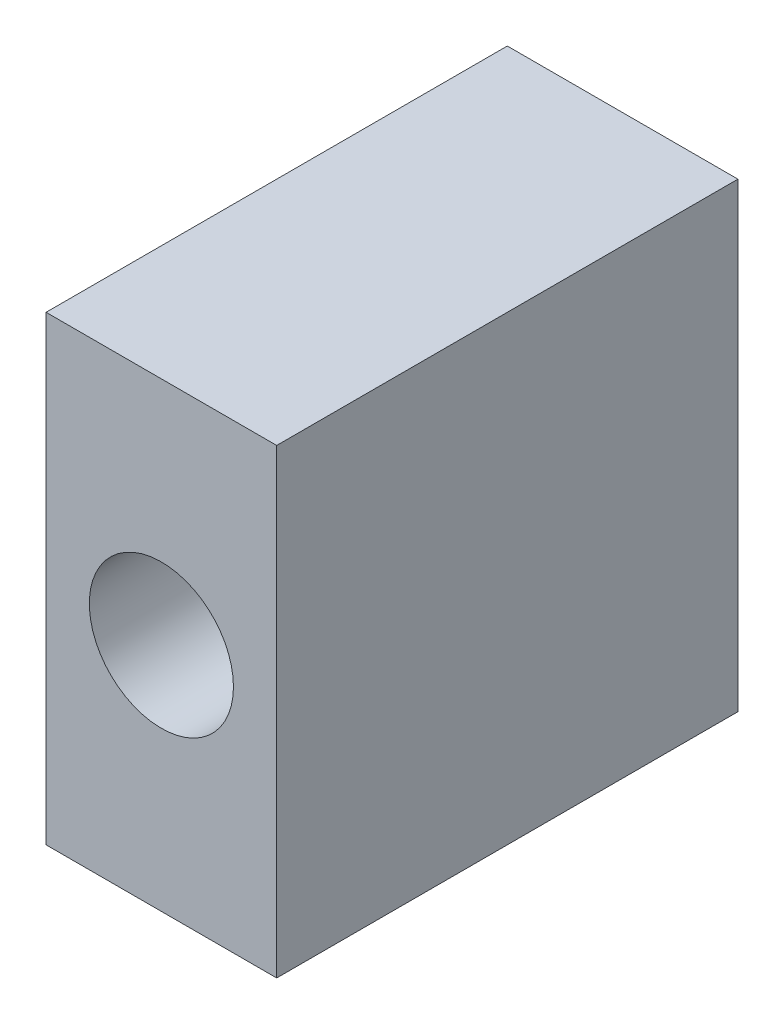
SolidWorks part; units mm, degrees
ref_plane "Front Plane" through (0, 0, 0) normal (0, 0, 1) x (1, 0, 0)
ref_plane "Top Plane" through (0, 0, 0) normal (0, 1, 0) x (1, 0, 0)
ref_plane "Right Plane" through (0, 0, 0) normal (1, 0, 0) x (0, 0, -1)
sketch "Sketch1" plane through (0, 0, 0) normal (0, 0, 1) x (1, 0, 0)
  line L1 (-2, 4) -> (2, 4)
  line L2 (-2, 4) -> (-2, -4)
  line L3 (-2, -4) -> (2, -4)
  line L4 (2, 4) -> (2, -4)
  circle A0 centre (0, 0) radius 1.25
  point P7 (0, 4)
  point P8 (0, 0)
  point P9 (0, 0)
  point P10 (2, 0)
  point P11 (0, 0)
  dimension "D1" = 2.5
  dimension "D2" = 8
  dimension "D3" = 4
extrude "Boss-Extrude1" add sketch "Sketch1" along normal blind 8
